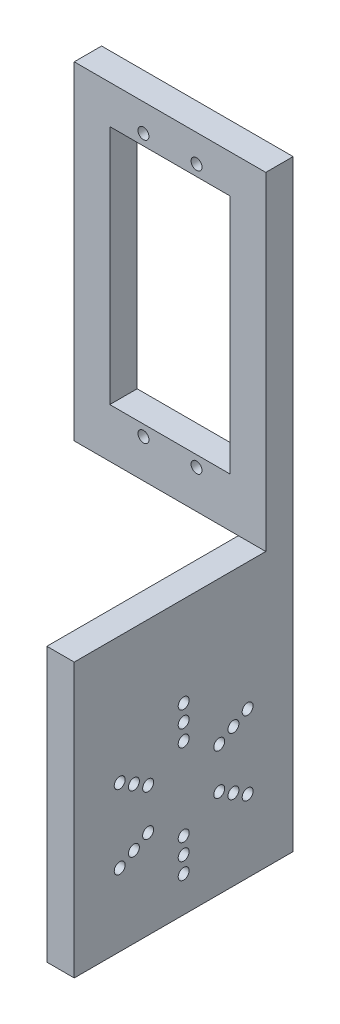
SolidWorks part; units mm, degrees
material "Polylactic Acid"
ref_plane "Front Plane" through (0, 0, 0) normal (0, 0, 1) x (1, 0, 0)
ref_plane "Top Plane" through (0, 0, 0) normal (0, 1, 0) x (1, 0, 0)
ref_plane "Right Plane" through (0, 0, 0) normal (1, 0, 0) x (0, 0, -1)
sketch "Sketch1" plane through (0, 0, 0) normal (0, 0, 1) x (1, 0, 0)
  line L0 (-4.85, -24) -> (4.85, -24) construction
  line L1 (-11, 22) -> (11, 22)
  line L2 (-11, 22) -> (-11, -22)
  line L3 (-11, -22) -> (11, -22)
  line L4 (11, 22) -> (11, -22)
  line L5 (-4.85, -24) -> (-4.85, 24) construction
  line L7 (-17.5, 29) -> (17.5, 29)
  line L8 (-17.5, 29) -> (-17.5, -31)
  line L9 (-17.5, -31) -> (17.5, -31)
  line L10 (17.5, 29) -> (17.5, -31)
  circle A0 centre (-4.85, -24) radius 1
  circle A1 centre (4.85, -24) radius 1
  circle A2 centre (4.85, 24) radius 1
  circle A3 centre (-4.85, 24) radius 1
  point P6 (-4.85, 0)
  point P8 (-11, 0)
  point P17 (0, -24)
  point P18 (0, -22)
  point P23 (0, -31)
  dimension "D7" = 2
  dimension "D1" = 9.7
  dimension "D2" = 48
  dimension "D3" = 22
  dimension "D4" = 44
  dimension "D8" = 35
  dimension "D9" = 60
  dimension "D10" = 7
  dimension "D5" = 2
  dimension "D6" = 2
extrude "Boss-Extrude1" add sketch "Sketch1" along normal blind 5
sketch "Sketch2" plane through (0, 0, 0) normal (0, 0, 1) x (1, 0, 0)
  line L1 (12.5, -31) -> (17.5, -31)
  line L2 (12.5, -31) -> (12.5, -81)
  line L3 (12.5, -81) -> (17.5, -81)
  line L4 (17.5, -31) -> (17.5, -81)
  dimension "D1" = 5
  dimension "D2" = 50
extrude "Boss-Extrude2" add sketch "Sketch2" along normal blind 40
sketch "Sketch3" plane through (17.5, 0, 0) normal (1, 0, 0) x (0, 0, -1)
  line L0 (-20, -74.5) -> (-20, -71.5) construction
  line L1 (-20, -61) -> (-20, -68.5) construction
  line L2 (-40, -81) -> (0, -81) construction
  circle A0 centre (-20, -74.5) radius 1
  circle A1 centre (-20, -71.5) radius 1
  circle A2 centre (-20, -68.5) radius 1
  circle A3 centre (-26.4952, -64.75) radius 1
  circle A4 centre (-29.0933, -66.25) radius 1
  circle A5 centre (-31.6913, -67.75) radius 1
  circle A6 centre (-26.4952, -57.25) radius 1
  circle A7 centre (-29.0933, -55.75) radius 1
  circle A8 centre (-31.6913, -54.25) radius 1
  circle A9 centre (-20, -53.5) radius 1
  circle A10 centre (-20, -50.5) radius 1
  circle A11 centre (-20, -47.5) radius 1
  circle A12 centre (-13.5048, -57.25) radius 1
  circle A13 centre (-10.9067, -55.75) radius 1
  circle A14 centre (-8.3087, -54.25) radius 1
  circle A15 centre (-13.5048, -64.75) radius 1
  circle A16 centre (-10.9067, -66.25) radius 1
  circle A17 centre (-8.3087, -67.75) radius 1
  point P33 (-20, -81)
  point P38 (0, 0)
  dimension "D3" = 2
  dimension "D1" = 3
  dimension "D4" = 7.5
  dimension "D6" = 20
  dimension "D2" = 3
  dimension "D5" = 6
extrude "Cut-Extrude1" cut sketch "Sketch3" against normal up to surface (35 mm away) up to face at (-17.5, -1, 2.5)
